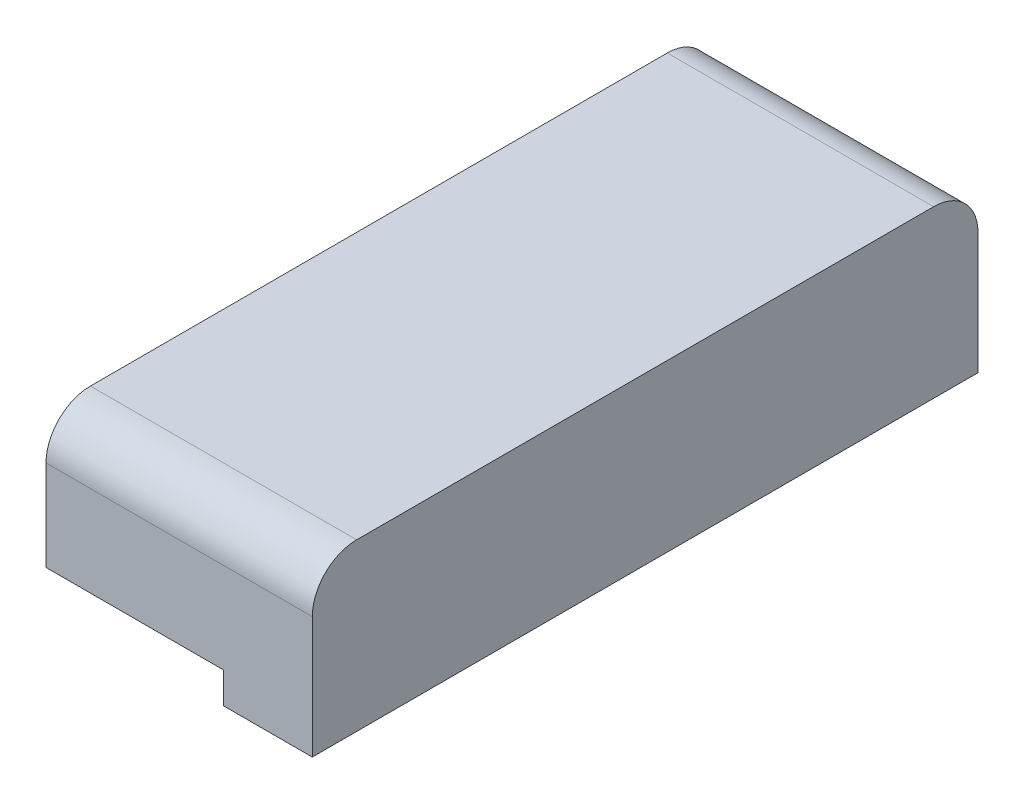
SolidWorks part; units mm, degrees
ref_plane "Alzado" through (0, 0, 0) normal (0, 0, 1) x (1, 0, 0)
ref_plane "Planta" through (0, 0, 0) normal (0, 1, 0) x (1, 0, 0)
ref_plane "Vista lateral" through (0, 0, 0) normal (1, 0, 0) x (0, 0, -1)
sketch "Croquis1" plane through (0, 0, 0) normal (1, 0, 0) x (0, 0, -1)
  line L1 (-3.75, 0.935) -> (3.75, 0.935)
  line L2 (-3.75, 0.935) -> (-3.75, -0.935)
  line L3 (-3.75, -0.935) -> (3.75, -0.935)
  line L4 (3.75, 0.935) -> (3.75, -0.935)
  line L5 (-3.75, 0.935) -> (3.75, -0.935) construction
  line L6 (-3.75, -0.935) -> (3.75, 0.935) construction
  point P0 (0, 0)
extrude "Saliente-Extruir1" add sketch "Croquis1" along normal blind 3
sketch "Croquis2" plane through (0, 0, 3.75) normal (0, 0, 1) x (1, 0, 0)
  line L1 (0, -0.935) -> (2, -0.935)
  line L2 (0, -0.935) -> (0, -0.585)
  line L3 (0, -0.585) -> (2, -0.585)
  line L4 (2, -0.935) -> (2, -0.585)
extrude "Cortar-Extruir1" cut sketch "Croquis2" against normal up to next
fillet "Redondeo1" radius 0.5 2 edges at (1.5, 0.935, -3.75) (1.5, 0.935, 3.75)
